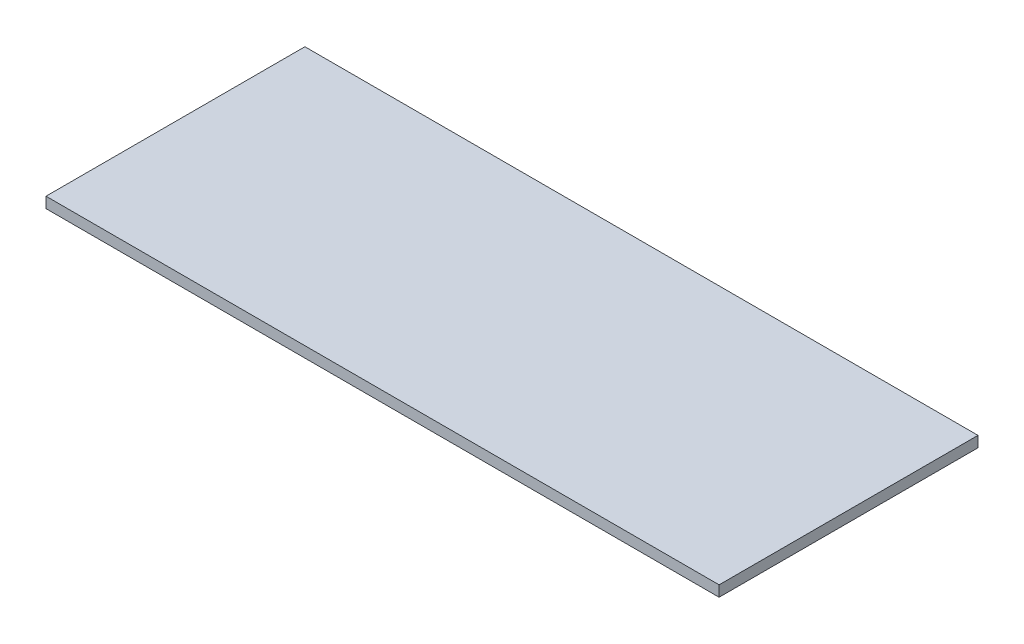
SolidWorks part; units mm, degrees
ref_plane "Front Plane" through (0, 0, 0) normal (0, 0, 1) x (1, 0, 0)
ref_plane "Top Plane" through (0, 0, 0) normal (0, 1, 0) x (1, 0, 0)
ref_plane "Right Plane" through (0, 0, 0) normal (1, 0, 0) x (0, 0, -1)
sketch "Sketch1" plane through (0, 0, 0) normal (0, 1, 0) x (1, 0, 0)
  line L1 (0, 0) -> (198.12, 0)
  line L2 (0, 0) -> (0, 76.2)
  line L3 (0, 76.2) -> (198.12, 76.2)
  line L4 (198.12, 0) -> (198.12, 76.2)
  dimension "D1" = 198.12
  dimension "D2" = 76.2
extrude "Boss-Extrude1" add sketch "Sketch1" along normal blind 3.175
